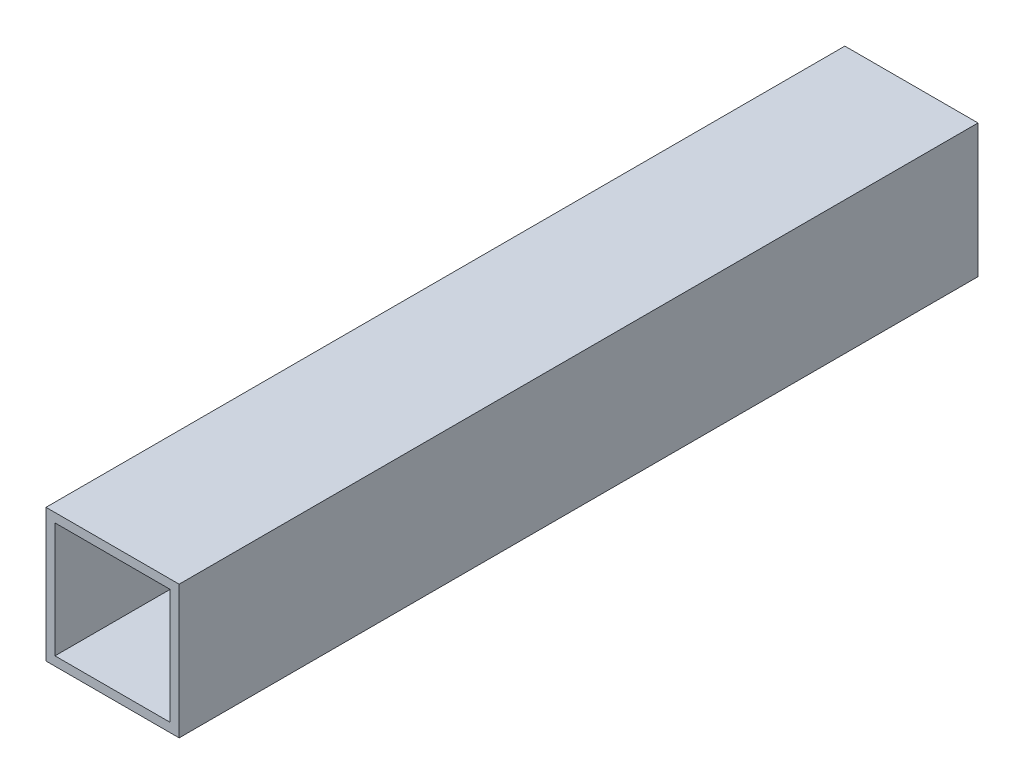
SolidWorks part; units mm, degrees
material "6063-O, Extruded Rod (SS)"
ref_plane "Front Plane" through (0, 0, 0) normal (0, 0, 1) x (1, 0, 0)
ref_plane "Top Plane" through (0, 0, 0) normal (0, 1, 0) x (1, 0, 0)
ref_plane "Right Plane" through (0, 0, 0) normal (1, 0, 0) x (0, 0, -1)
sketch "Sketch1" plane through (0, 0, 0) normal (0, 0, 1) x (1, 0, 0)
  line L0 (-10.9855, 10.9855) -> (10.9855, 10.9855)
  line L1 (-12.7, -12.7) -> (12.7, -12.7)
  line L2 (-12.7, -12.7) -> (-12.7, 12.7)
  line L3 (-12.7, 12.7) -> (12.7, 12.7)
  line L4 (12.7, -12.7) -> (12.7, 12.7)
  line L5 (-12.7, -12.7) -> (12.7, 12.7) construction
  line L6 (-12.7, 12.7) -> (12.7, -12.7) construction
  line L7 (10.9855, -10.9855) -> (10.9855, 10.9855)
  line L8 (-10.9855, -10.9855) -> (10.9855, -10.9855)
  line L9 (-10.9855, -10.9855) -> (-10.9855, 10.9855)
  point P0 (0, 0)
  dimension "D1" = 25.4
  dimension "D2" = 25.4
  dimension "D3" = 1.7145
extrude "Boss-Extrude1" add sketch "Sketch1" along normal mid plane 152.4
